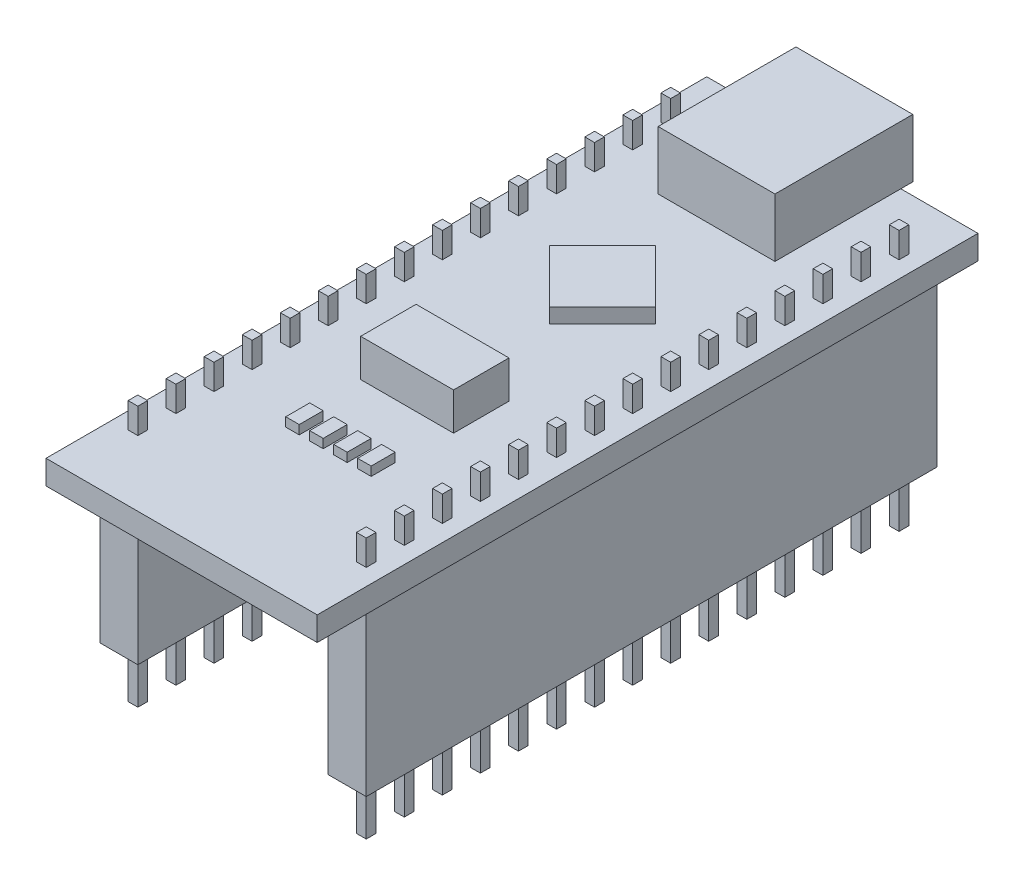
SolidWorks part; units mm, degrees
ref_plane "Plan de face" through (0, 0, 0) normal (0, 0, 1) x (1, 0, 0)
ref_plane "Plan de dessus" through (0, 0, 0) normal (0, 1, 0) x (1, 0, 0)
ref_plane "Plan de droite" through (0, 0, 0) normal (1, 0, 0) x (0, 0, -1)
sketch "Esquisse1" plane through (0, 0, 0) normal (0, 1, 0) x (1, 0, 0)
  line L1 (-9.05, 22.05) -> (9.05, 22.05)
  line L2 (-9.05, 22.05) -> (-9.05, -22.05)
  line L3 (-9.05, -22.05) -> (9.05, -22.05)
  line L4 (9.05, 22.05) -> (9.05, -22.05)
  point P4 (0, 22.05)
  point P6 (-9.05, 0)
  dimension "D1" = 18.1
  dimension "D2" = 44.1
extrude "Boss.-Extru.1" add sketch "Esquisse1" along normal blind 1.6
sketch "Esquisse2" plane through (0, 0, 0) normal (0, -1, 0) x (1, 0, 0)
  line L0 (0, 0) -> (0, 5.1408) construction
  line L1 (-7.945, 17.675) -> (-7.295, 17.675)
  line L2 (-7.945, 17.675) -> (-7.945, 17.025)
  line L3 (-7.945, 17.025) -> (-7.295, 17.025)
  line L4 (-7.295, 17.675) -> (-7.295, 17.025)
  line L5 (0, 0) -> (2.9882, 0) construction
  line L6 (7.295, 17.675) -> (7.295, 17.025)
  line L7 (7.945, 17.025) -> (7.295, 17.025)
  line L8 (7.945, 17.675) -> (7.945, 17.025)
  line L9 (7.945, 17.675) -> (7.295, 17.675)
  line L10 (-9.05, 22.05) -> (9.05, 22.05) construction
  line L11 (-7.945, 15.135) -> (-7.945, 14.485)
  line L12 (-7.945, 15.135) -> (-7.295, 15.135)
  line L13 (-7.295, 15.135) -> (-7.295, 14.485)
  line L14 (-7.945, 14.485) -> (-7.295, 14.485)
  line L15 (7.945, 15.135) -> (7.295, 15.135)
  line L16 (7.295, 15.135) -> (7.295, 14.485)
  line L17 (7.945, 14.485) -> (7.295, 14.485)
  line L18 (7.945, 15.135) -> (7.945, 14.485)
  line L19 (-7.945, 12.595) -> (-7.945, 11.945)
  line L20 (-7.945, 12.595) -> (-7.295, 12.595)
  line L21 (-7.295, 12.595) -> (-7.295, 11.945)
  line L22 (-7.945, 11.945) -> (-7.295, 11.945)
  line L23 (7.945, 12.595) -> (7.295, 12.595)
  line L24 (7.295, 12.595) -> (7.295, 11.945)
  line L25 (7.945, 11.945) -> (7.295, 11.945)
  line L26 (7.945, 12.595) -> (7.945, 11.945)
  line L27 (-7.945, 10.055) -> (-7.945, 9.405)
  line L28 (-7.945, 10.055) -> (-7.295, 10.055)
  line L29 (-7.295, 10.055) -> (-7.295, 9.405)
  line L30 (-7.945, 9.405) -> (-7.295, 9.405)
  line L31 (7.945, 10.055) -> (7.295, 10.055)
  line L32 (7.295, 10.055) -> (7.295, 9.405)
  line L33 (7.945, 9.405) -> (7.295, 9.405)
  line L34 (7.945, 10.055) -> (7.945, 9.405)
  line L35 (-7.945, 7.515) -> (-7.945, 6.865)
  line L36 (-7.945, 7.515) -> (-7.295, 7.515)
  line L37 (-7.295, 7.515) -> (-7.295, 6.865)
  line L38 (-7.945, 6.865) -> (-7.295, 6.865)
  line L39 (7.945, 7.515) -> (7.295, 7.515)
  line L40 (7.295, 7.515) -> (7.295, 6.865)
  line L41 (7.945, 6.865) -> (7.295, 6.865)
  line L42 (7.945, 7.515) -> (7.945, 6.865)
  line L43 (-7.945, 4.975) -> (-7.945, 4.325)
  line L44 (-7.945, 4.975) -> (-7.295, 4.975)
  line L45 (-7.295, 4.975) -> (-7.295, 4.325)
  line L46 (-7.945, 4.325) -> (-7.295, 4.325)
  line L47 (7.945, 4.975) -> (7.295, 4.975)
  line L48 (7.295, 4.975) -> (7.295, 4.325)
  line L49 (7.945, 4.325) -> (7.295, 4.325)
  line L50 (7.945, 4.975) -> (7.945, 4.325)
  line L51 (-7.945, 2.435) -> (-7.945, 1.785)
  line L52 (-7.945, 2.435) -> (-7.295, 2.435)
  line L53 (-7.295, 2.435) -> (-7.295, 1.785)
  line L54 (-7.945, 1.785) -> (-7.295, 1.785)
  line L55 (7.945, 2.435) -> (7.295, 2.435)
  line L56 (7.295, 2.435) -> (7.295, 1.785)
  line L57 (7.945, 1.785) -> (7.295, 1.785)
  line L58 (7.945, 2.435) -> (7.945, 1.785)
  line L59 (-7.945, -0.105) -> (-7.945, -0.755)
  line L60 (-7.945, -0.105) -> (-7.295, -0.105)
  line L61 (-7.295, -0.105) -> (-7.295, -0.755)
  line L62 (-7.945, -0.755) -> (-7.295, -0.755)
  line L63 (7.945, -0.105) -> (7.295, -0.105)
  line L64 (7.295, -0.105) -> (7.295, -0.755)
  line L65 (7.945, -0.755) -> (7.295, -0.755)
  line L66 (7.945, -0.105) -> (7.945, -0.755)
  line L67 (-7.945, -2.645) -> (-7.945, -3.295)
  line L68 (-7.945, -2.645) -> (-7.295, -2.645)
  line L69 (-7.295, -2.645) -> (-7.295, -3.295)
  line L70 (-7.945, -3.295) -> (-7.295, -3.295)
  line L71 (7.945, -2.645) -> (7.295, -2.645)
  line L72 (7.295, -2.645) -> (7.295, -3.295)
  line L73 (7.945, -3.295) -> (7.295, -3.295)
  line L74 (7.945, -2.645) -> (7.945, -3.295)
  line L75 (-7.945, -5.185) -> (-7.945, -5.835)
  line L76 (-7.945, -5.185) -> (-7.295, -5.185)
  line L77 (-7.295, -5.185) -> (-7.295, -5.835)
  line L78 (-7.945, -5.835) -> (-7.295, -5.835)
  line L79 (7.945, -5.185) -> (7.295, -5.185)
  line L80 (7.295, -5.185) -> (7.295, -5.835)
  line L81 (7.945, -5.835) -> (7.295, -5.835)
  line L82 (7.945, -5.185) -> (7.945, -5.835)
  line L83 (-7.945, -7.725) -> (-7.945, -8.375)
  line L84 (-7.945, -7.725) -> (-7.295, -7.725)
  line L85 (-7.295, -7.725) -> (-7.295, -8.375)
  line L86 (-7.945, -8.375) -> (-7.295, -8.375)
  line L87 (7.945, -7.725) -> (7.295, -7.725)
  line L88 (7.295, -7.725) -> (7.295, -8.375)
  line L89 (7.945, -8.375) -> (7.295, -8.375)
  line L90 (7.945, -7.725) -> (7.945, -8.375)
  line L91 (-7.945, -10.265) -> (-7.945, -10.915)
  line L92 (-7.945, -10.265) -> (-7.295, -10.265)
  line L93 (-7.295, -10.265) -> (-7.295, -10.915)
  line L94 (-7.945, -10.915) -> (-7.295, -10.915)
  line L95 (7.945, -10.265) -> (7.295, -10.265)
  line L96 (7.295, -10.265) -> (7.295, -10.915)
  line L97 (7.945, -10.915) -> (7.295, -10.915)
  line L98 (7.945, -10.265) -> (7.945, -10.915)
  line L99 (-7.945, -12.805) -> (-7.945, -13.455)
  line L100 (-7.945, -12.805) -> (-7.295, -12.805)
  line L101 (-7.295, -12.805) -> (-7.295, -13.455)
  line L102 (-7.945, -13.455) -> (-7.295, -13.455)
  line L103 (7.945, -12.805) -> (7.295, -12.805)
  line L104 (7.295, -12.805) -> (7.295, -13.455)
  line L105 (7.945, -13.455) -> (7.295, -13.455)
  line L106 (7.945, -12.805) -> (7.945, -13.455)
  line L107 (-7.945, -15.345) -> (-7.945, -15.995)
  line L108 (-7.945, -15.345) -> (-7.295, -15.345)
  line L109 (-7.295, -15.345) -> (-7.295, -15.995)
  line L110 (-7.945, -15.995) -> (-7.295, -15.995)
  line L111 (7.945, -15.345) -> (7.295, -15.345)
  line L112 (7.295, -15.345) -> (7.295, -15.995)
  line L113 (7.945, -15.995) -> (7.295, -15.995)
  line L114 (7.945, -15.345) -> (7.945, -15.995)
  line L115 (-7.945, -17.885) -> (-7.945, -18.535)
  line L116 (-7.945, -17.885) -> (-7.295, -17.885)
  line L117 (-7.295, -17.885) -> (-7.295, -18.535)
  line L118 (-7.945, -18.535) -> (-7.295, -18.535)
  line L119 (7.945, -17.885) -> (7.295, -17.885)
  line L120 (7.295, -17.885) -> (7.295, -18.535)
  line L121 (7.945, -18.535) -> (7.295, -18.535)
  line L122 (7.945, -17.885) -> (7.945, -18.535)
  point P12 (-7.62, 17.675)
  point P13 (7.62, 17.675)
  point P14 (-7.945, 17.35)
  dimension "D1" = 0.65
  dimension "D2" = 15.24
  dimension "D3" = 4.7
  dimension "D4" = 15
extrude "Boss.-Extru.2" add sketch "Esquisse2" along normal blind 14.1 and the other way blind 3.3 separate body
sketch "Esquisse3" plane through (0, 0, 0) normal (0, -1, 0) x (1, 0, 0)
  line L1 (-8.89, 18.62) -> (-6.35, 18.62)
  line L2 (-8.89, 18.62) -> (-8.89, -19.48)
  line L3 (-8.89, -19.48) -> (-6.35, -19.48)
  line L4 (-6.35, 18.62) -> (-6.35, -19.48)
  line L5 (0, 0) -> (0, 4.7556) construction
  line L6 (-7.295, 17.675) -> (-7.945, 17.675) construction
  line L7 (-7.295, -0.755) -> (-7.295, -0.105) construction
  line L8 (6.35, 18.62) -> (6.35, -19.48)
  line L9 (8.89, -19.48) -> (6.35, -19.48)
  line L10 (8.89, 18.62) -> (8.89, -19.48)
  line L11 (8.89, 18.62) -> (6.35, 18.62)
  point P10 (-7.62, 17.675)
  point P11 (-7.62, 18.62)
  point P13 (-7.295, -0.43)
  point P14 (-6.35, -0.43)
  dimension "D1" = 2.54
  dimension "D2" = 38.1
extrude "Boss.-Extru.3" add sketch "Esquisse3" along normal blind 10.7 separate body
sketch "Esquisse4" plane through (0, 1.6, 0) normal (0, 1, 0) x (1, 0, 0)
  line L0 (9.05, 22.05) -> (-9.05, 22.05) construction
  line L1 (-3.9, 22.85) -> (3.9, 22.85)
  line L2 (-3.9, 22.85) -> (-3.9, 13.65)
  line L3 (-3.9, 13.65) -> (3.9, 13.65)
  line L4 (3.9, 22.85) -> (3.9, 13.65)
  point P4 (0, 13.65)
  dimension "D1" = 7.8
  dimension "D2" = 9.2
  dimension "D3" = 0.8
extrude "Boss.-Extru.4" add sketch "Esquisse4" along normal blind 3.9 separate body
sketch "Esquisse5" plane through (0, 1.6, 0) normal (0, 1, 0) x (1, 0, 0)
  line L0 (-3.5355, 6.05) -> (0, 9.5855)
  line L1 (0, 9.5855) -> (3.5355, 6.05)
  line L2 (3.5355, 6.05) -> (0, 2.5145)
  line L3 (0, 2.5145) -> (-3.5355, 6.05)
  line L4 (9.05, 22.05) -> (-9.05, 22.05) construction
  dimension "D1" = 5
  dimension "D2" = 16
extrude "Boss.-Extru.5" add sketch "Esquisse5" along normal blind 1 separate body
sketch "Esquisse6" plane through (0, 1.6, 0) normal (0, 1, 0) x (1, 0, 0)
  line L0 (9.05, 22.05) -> (-9.05, 22.05) construction
  line L1 (-3.1, -3.3) -> (3.1, -3.3)
  line L2 (-3.1, -3.3) -> (-3.1, -7)
  line L3 (-3.1, -7) -> (3.1, -7)
  line L4 (3.1, -3.3) -> (3.1, -7)
  point P4 (0, -3.3)
  point P6 (-3.1, -5.15)
  dimension "D1" = 3.7
  dimension "D2" = 6.2
  dimension "D3" = 27.2
extrude "Boss.-Extru.6" add sketch "Esquisse6" along normal blind 2.5 separate body
sketch "Esquisse7" plane through (0, 1.6, 0) normal (0, 1, 0) x (1, 0, 0)
  line L0 (0, 0) -> (0, -1.9107) construction
  line L1 (-2.85, -10.65) -> (-1.95, -10.65)
  line L2 (-2.85, -10.65) -> (-2.85, -12.25)
  line L3 (-2.85, -12.25) -> (-1.95, -12.25)
  line L4 (-1.95, -10.65) -> (-1.95, -12.25)
  line L5 (-1.25, -10.65) -> (-0.35, -10.65)
  line L6 (-1.25, -10.65) -> (-1.25, -12.25)
  line L7 (-1.25, -12.25) -> (-0.35, -12.25)
  line L8 (-0.35, -10.65) -> (-0.35, -12.25)
  line L9 (0.35, -10.65) -> (0.35, -12.25)
  line L10 (1.25, -12.25) -> (0.35, -12.25)
  line L11 (1.25, -10.65) -> (1.25, -12.25)
  line L12 (1.25, -10.65) -> (0.35, -10.65)
  line L13 (1.95, -10.65) -> (1.95, -12.25)
  line L14 (2.85, -12.25) -> (1.95, -12.25)
  line L15 (2.85, -10.65) -> (2.85, -12.25)
  line L16 (2.85, -10.65) -> (1.95, -10.65)
  line L17 (9.05, 22.05) -> (-9.05, 22.05) construction
  point P19 (-2.85, -11.45)
  dimension "D1" = 0.7
  dimension "D2" = 0.7
  dimension "D3" = 0.9
  dimension "D4" = 1.6
  dimension "D5" = 33.5
extrude "Boss.-Extru.7" add sketch "Esquisse7" along normal blind 0.6 separate body
sketch "Esquisse8" plane through (0, 0, 0) normal (0, -1, 0) x (1, 0, 0)
  line L0 (9.05, -22.05) -> (-9.05, -22.05) construction
  line L1 (-3.0339, -4.05) -> (3.0339, -4.05)
  line L2 (-3.0339, -4.05) -> (-3.0339, -14.25)
  line L3 (-3.0339, -14.25) -> (3.0339, -14.25)
  line L4 (3.0339, -4.05) -> (3.0339, -14.25)
  line L5 (-5.2097, 13.85) -> (0.2903, 13.85)
  line L6 (-5.2097, 13.85) -> (-5.2097, 9.75)
  line L7 (-5.2097, 9.75) -> (0.2903, 9.75)
  line L8 (0.2903, 13.85) -> (0.2903, 9.75)
  line L9 (3.9839, 13.85) -> (2.5742, 13.85)
  line L10 (3.9839, 13.85) -> (3.9839, 9.75)
  line L11 (3.9839, 9.75) -> (2.5742, 9.75)
  line L12 (2.5742, 13.85) -> (2.5742, 9.75)
  point P4 (0, -4.05)
  dimension "D1" = 10.2
  dimension "D2" = 4.1
  dimension "D3" = 7.8
  dimension "D4" = 31.8
  dimension "D5" = 5.5
extrude "Boss.-Extru.8" add sketch "Esquisse8" along normal blind 1.7 separate body
equation "\"D2@Esquisse7\"=\"D1@Esquisse7\""
